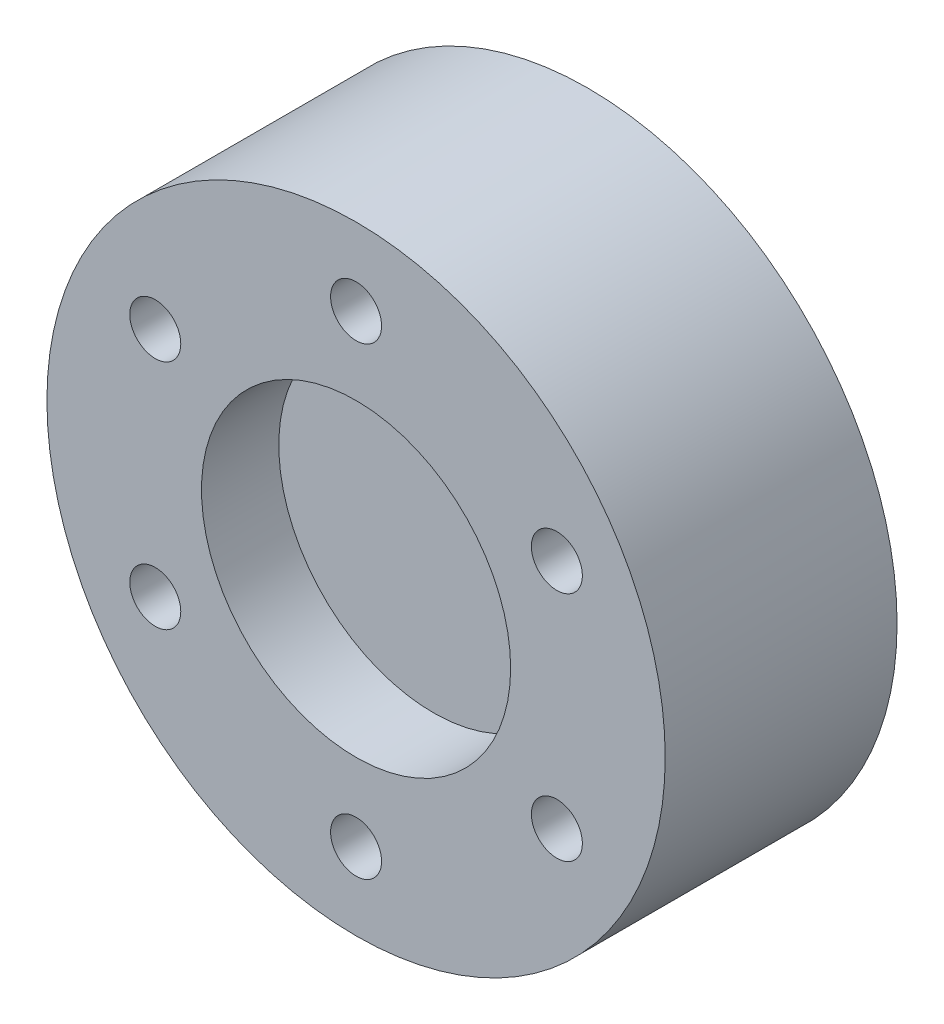
SolidWorks part; units mm, degrees
ref_plane "Front Plane" through (0, 0, 0) normal (0, 0, 1) x (1, 0, 0)
ref_plane "Top Plane" through (0, 0, 0) normal (0, 1, 0) x (1, 0, 0)
ref_plane "Right Plane" through (0, 0, 0) normal (1, 0, 0) x (0, 0, -1)
sketch "Sketch1" plane through (0, 0, 0) normal (0, 0, 1) x (1, 0, 0)
  circle A0 centre (0, 0) radius 20
  dimension "D1" = 40
extrude "Boss-Extrude1" add sketch "Sketch1" along normal blind 15
sketch "Sketch2" plane through (0, 0, 15) normal (0, 0, 1) x (1, 0, 0)
  circle A0 centre (0, 0) radius 10
  dimension "D1" = 20
extrude "Cut-Extrude1" cut sketch "Sketch2" against normal blind 5
hole_wizard "M4x0.7 Tapped Hole1" positions "Sketch3" profile "Sketch4" tap size "M4x0.7" standard "ANSI Metric"
sketch "Sketch3" plane through (0, 0, 15) normal (0, 0, 1) x (1, 0, 0)
  point P0 (0, 15)
  dimension "D1" = 15
sketch "Sketch4" plane through (0, 15, 15) normal (1, 0, 0) x (0, -1, 0)
  line L0 (0, 0) -> (0, 8.0914)
  line L1 (0, 8.0914) -> (1.65, 7.1)
  line L2 (1.65, 7.1) -> (1.65, 0)
  line L5 (1.65, 0) -> (0, 0)
  line L10 (0, 8.0914) -> (-1.65, 7.1) construction
  line L11 (0, -6.35) -> (0, 107.95) construction
  dimension "Tap Drill Dia." = 3.3
  dimension "Tap Drill Depth" = 7.1
  dimension "Drill Angle" = 118
cosmetic thread "Hole Thread1" parameters "D1"=5, "D2"=4
pattern_circular "CirPattern1" count 6 over 360 about axis through (0, 0, 0) along (0, 0, 1) of "M4x0.7 Tapped Hole1"
sketch "Sketch5" plane through (0, 0, 0) normal (0, 0, -1) x (-1, 0, 0)
  circle A0 centre (0, 0) radius 17.5
  dimension "D1" = 35
extrude "Cut-Extrude2" cut sketch "Sketch5" against normal blind 3
